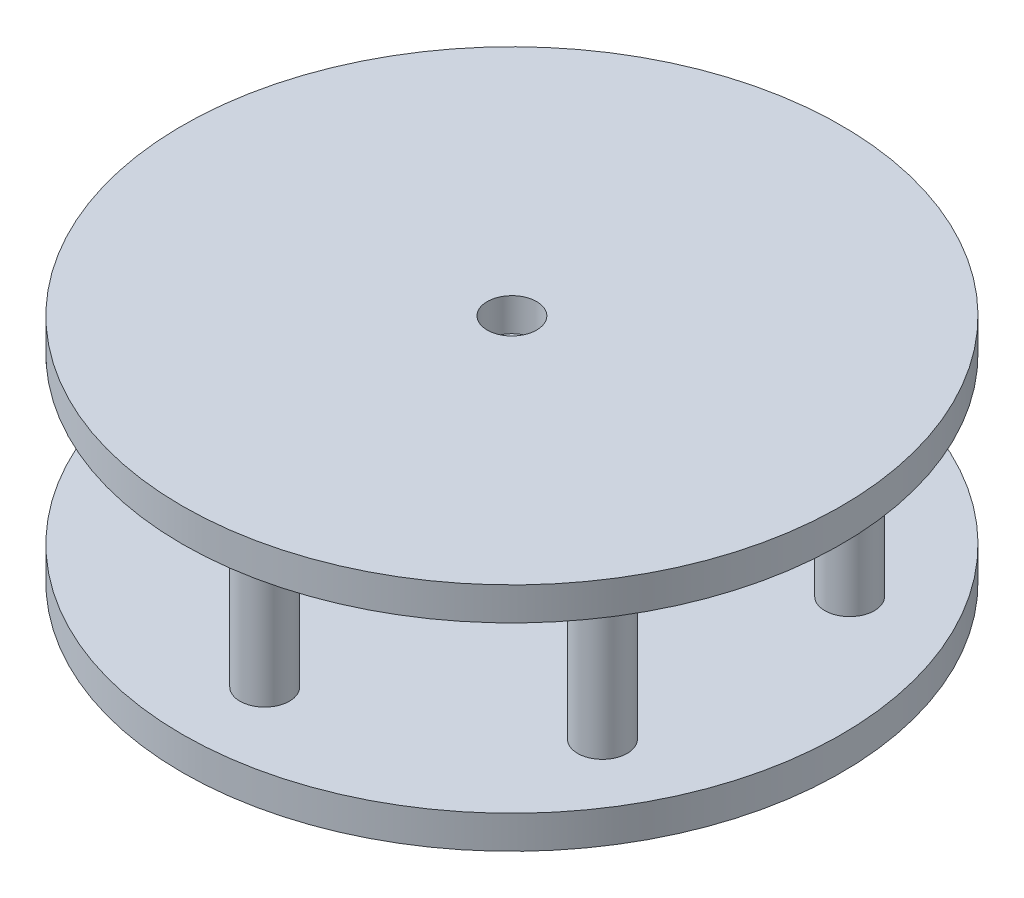
SolidWorks part; units mm, degrees
ref_plane "Front Plane" through (0, 0, 0) normal (0, 0, 1) x (1, 0, 0)
ref_plane "Top Plane" through (0, 0, 0) normal (0, 1, 0) x (1, 0, 0)
ref_plane "Right Plane" through (0, 0, 0) normal (1, 0, 0) x (0, 0, -1)
sketch "Sketch1" plane through (0, 0, 0) normal (0, 1, 0) x (1, 0, 0)
  circle A0 centre (0, 0) radius 50.7896
extrude "Boss-Extrude1" add sketch "Sketch1" along normal blind 5.08
sketch "Sketch3" plane through (0, 5.08, 0) normal (0, 1, 0) x (1, 0, 0)
  line L0 (0, 38.1) -> (0, 0)
  circle A0 centre (0, 38.1) radius 3.8137
  dimension "D1" = 7.6275
  dimension "D2" = 38.1
extrude "Boss-Extrude2" add sketch "Sketch3" along normal blind 25.4
pattern_circular "CirPattern1" count 6 over 360 about axis through (0, 0, 0) along (0, 1, 0) of "Boss-Extrude2"
sketch "Sketch4" plane through (0, 30.48, 0) normal (0, 1, 0) x (1, 0, 0)
  line L0 (-32.9956, -19.05) -> (0, 0)
  circle A0 centre (0, 0) radius 50.7896
extrude "Boss-Extrude3" add sketch "Sketch4" along normal blind 5.08 contours A0
sketch "Sketch6" plane through (0, 35.56, 0) normal (0, 1, 0) x (1, 0, 0)
  circle A0 centre (0, 0) radius 3.81
  dimension "D1" = 7.62
extrude "Cut-Extrude1" cut sketch "Sketch6" against normal through all
